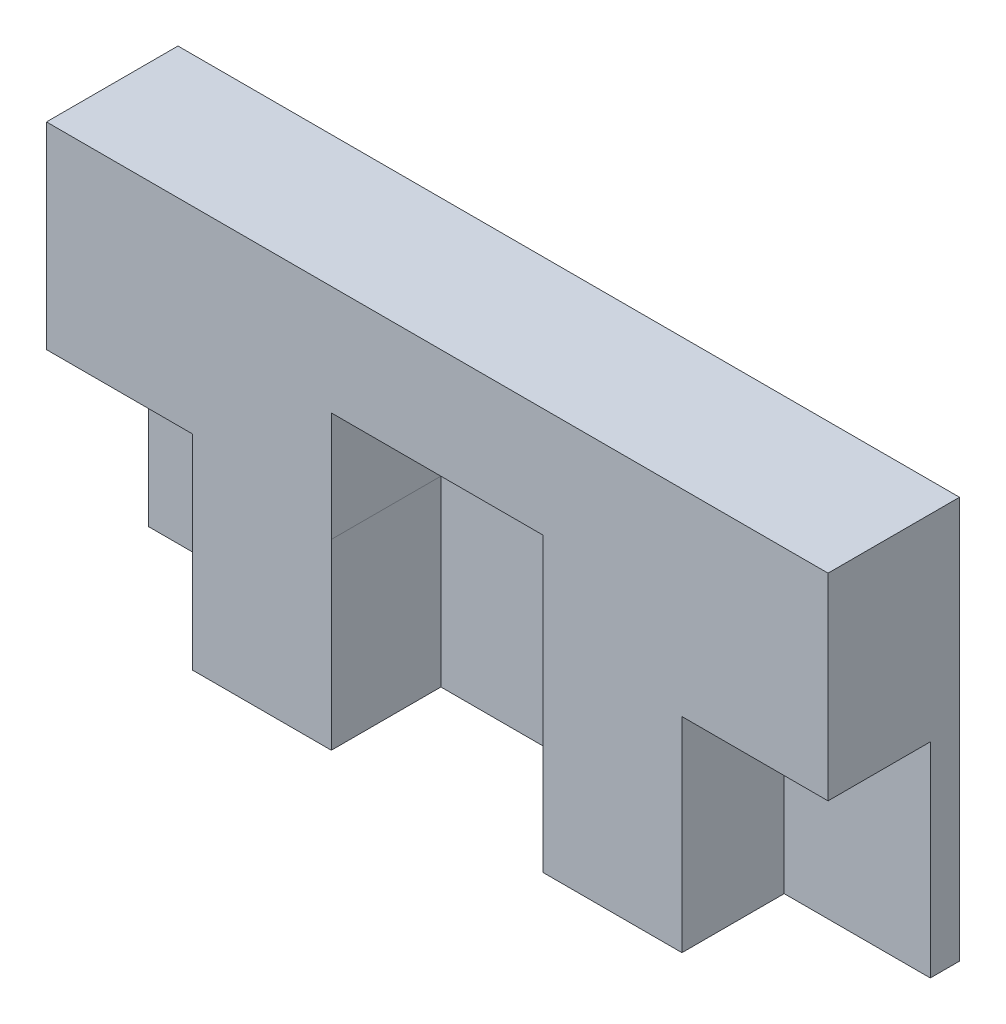
SolidWorks part; units mm, degrees
ref_plane "Front Plane" through (0, 0, 0) normal (0, 0, 1) x (1, 0, 0)
ref_plane "Top Plane" through (0, 0, 0) normal (0, 1, 0) x (1, 0, 0)
ref_plane "Right Plane" through (0, 0, 0) normal (1, 0, 0) x (0, 0, -1)
sketch "Sketch1" plane through (0, 0, 0) normal (0, 1, 0) x (1, 0, 0)
  line L1 (-339.725, 0) -> (339.725, 0)
  line L2 (-339.725, 0) -> (-339.725, 114.3)
  line L3 (-339.725, 114.3) -> (339.725, 114.3)
  line L4 (339.725, 0) -> (339.725, 114.3)
  point P6 (0, 0)
  dimension "D1" = 679.45
  dimension "D2" = 114.3
extrude "Boss-Extrude1" add sketch "Sketch1" along normal blind 349.25
sketch "Sketch2" plane through (0, 0, 0) normal (1, 0, 0) x (0, 0, -1)
  line L0 (47.625, 0) -> (47.625, 158.75)
  line L1 (0, 0) -> (114.3, 0) construction
  line L2 (0, 349.25) -> (0, 0) construction
  line L3 (0, 206.375) -> (-25.4, 206.375)
  line L4 (0, 349.25) -> (114.3, 349.25) construction
  arc A0 (47.625, 158.75) -> (0, 206.375) centre (0, 158.75) ccw
  dimension "D1" = 47.625
  dimension "D2" = 25.4
  dimension "D3" = 142.875
sketch "Sketch4" plane through (0, 0, 0) normal (0, 1, 0) x (1, 0, 0)
  line L0 (-339.725, 0) -> (339.725, 0) construction
  line L1 (-92.075, 0) -> (92.075, 0)
  line L2 (-92.075, 0) -> (-92.075, 95.25)
  line L3 (-92.075, 95.25) -> (92.075, 95.25)
  line L4 (92.075, 0) -> (92.075, 95.25)
  point P6 (92.075, 47.625)
  point P8 (0, 95.25)
  dimension "D1" = 184.15
sweep "Cut-Sweep4" cut profiles "Sketch4" path "Sketch2"
sketch "Sketch5" plane through (0, 0, 0) normal (0, 1, 0) x (1, 0, 0)
  line L0 (0, 0) -> (0, 95.25) construction
  line L1 (-339.725, 0) -> (-212.725, 0)
  line L2 (-339.725, 0) -> (-339.725, 88.9)
  line L3 (-339.725, 88.9) -> (-212.725, 88.9)
  line L4 (-212.725, 0) -> (-212.725, 88.9)
  line L7 (339.725, 88.9) -> (212.725, 88.9)
  line L8 (339.725, 0) -> (339.725, 88.9)
  line L9 (339.725, 0) -> (212.725, 0)
  line L10 (212.725, 0) -> (212.725, 88.9)
  dimension "D1" = 127
  dimension "D2" = 88.9
extrude "Cut-Extrude1" cut sketch "Sketch5" along normal blind 177.8
